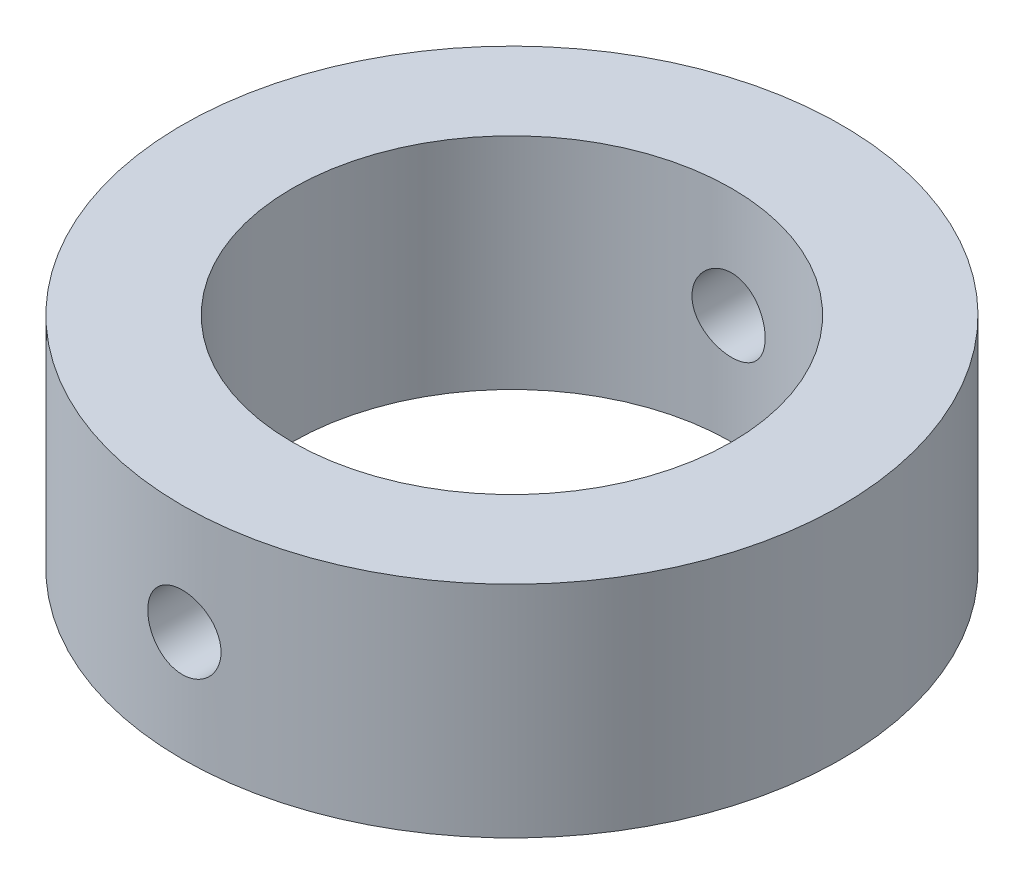
SolidWorks part; units mm, degrees
ref_plane "Front Plane" through (0, 0, 0) normal (0, 0, 1) x (1, 0, 0)
ref_plane "Top Plane" through (0, 0, 0) normal (0, 1, 0) x (1, 0, 0)
ref_plane "Right Plane" through (0, 0, 0) normal (1, 0, 0) x (0, 0, -1)
sketch "Sketch1" plane through (0, 0, 0) normal (0, 1, 0) x (1, 0, 0)
  circle A0 centre (0, 0) radius 15
  circle A1 centre (0, 0) radius 22.5
  dimension "D1" = 45
  dimension "D2" = 30
extrude "Boss-Extrude1" add sketch "Sketch1" along normal mid plane 15
sketch "Sketch2" plane through (0, 0, 0) normal (0, 0, 1) x (1, 0, 0)
  circle A0 centre (0, 0) radius 2.4995
extrude "Cut-Extrude1" cut sketch "Sketch2" against normal through all both and the other way through all
